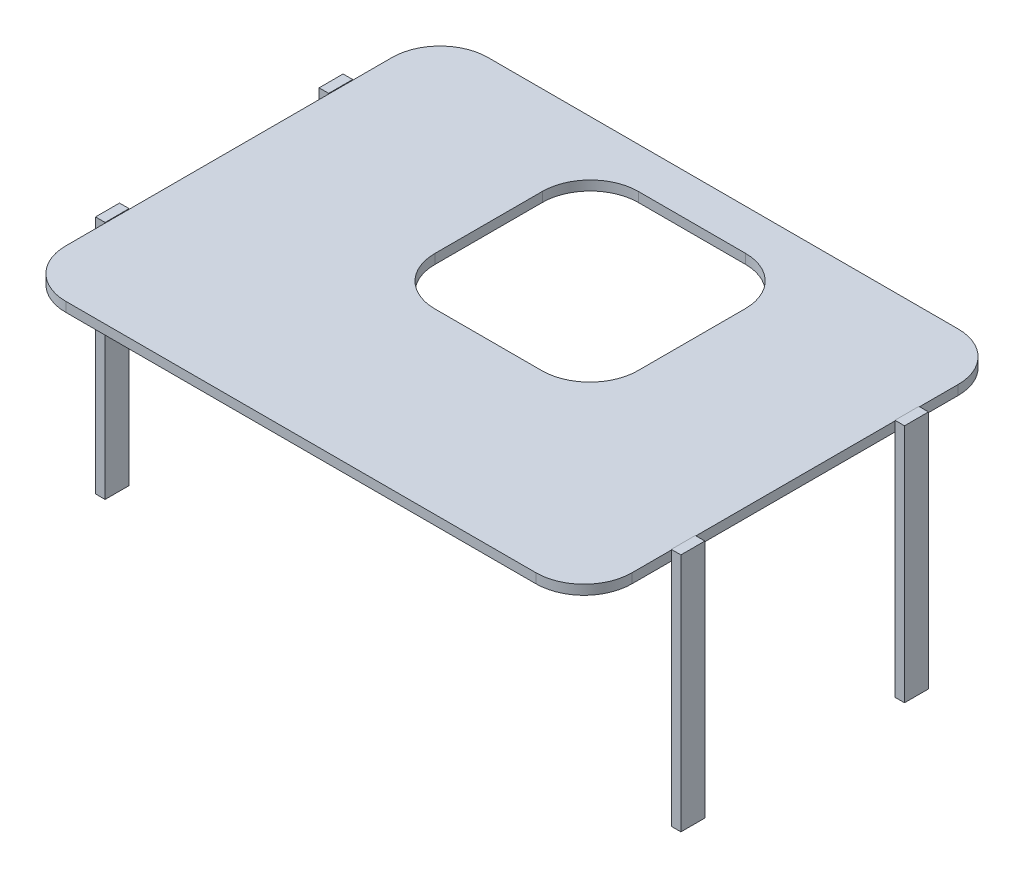
SolidWorks part; units mm, degrees
ref_plane "Plano frontal" through (0, 0, 0) normal (0, 0, 1) x (1, 0, 0)
ref_plane "Plano superior" through (0, 0, 0) normal (0, 1, 0) x (1, 0, 0)
ref_plane "Plano direito" through (0, 0, 0) normal (1, 0, 0) x (0, 0, -1)
sketch "Esboço1" plane through (0, 0, 0) normal (0, 1, 0) x (1, 0, 0)
  line L1 (-59, 44) -> (59, 44)
  line L2 (-59, 44) -> (-59, -44)
  line L3 (-59, -44) -> (59, -44)
  line L4 (59, 44) -> (59, -44)
  line L5 (-59, 44) -> (59, -44) construction
  line L6 (-59, -44) -> (59, 44) construction
  point P0 (0, 0)
  dimension "D1" = 88
  dimension "D2" = 118
extrude "Ressalto-extrusão1" add sketch "Esboço1" along normal blind 2
fillet "Filete1" radius 10 1 edges at (59, 1, -44)
fillet "Filete2" radius 10 3 edges at (-59, 1, 44) (-59, 1, -44) (59, 1, 44)
sketch "Esboço2" plane through (0, 0, 0) normal (0, 1, 0) x (1, 0, 0)
  line L0 (49, 44) -> (-49, 44) construction
  line L1 (-19.17, 35.49) -> (23.14, 35.49)
  line L2 (-19.17, 35.49) -> (-19.17, -6.91)
  line L3 (-19.17, -6.91) -> (23.14, -6.91)
  line L4 (23.14, 35.49) -> (23.14, -6.91)
  line L5 (-59, 34) -> (-59, -34) construction
  dimension "D1" = 42.4
  dimension "D2" = 42.31
  dimension "D3" = 8.51
  dimension "D4" = 39.83
extrude "Corte-extrusão2" cut sketch "Esboço2" along normal blind 2
fillet "Filete3" radius 10 4 edges at (-19.17, 1, 6.91) (23.14, 1, 6.91) (23.14, 1, -35.49) (-19.17, 1, -35.49)
ref_plane "Plano1" through (69, 0, 0) normal (1, 0, 0) x (0, 0, -1)
sketch "Esboço5" plane through (59, 0, 0) normal (1, 0, 0) x (0, 0, -1)
  line L0 (-44, 2) -> (-44, 0) construction
  line L1 (-25.8, 2.1292) -> (-20.8, 2.1292)
  line L2 (-25.8, 2.1292) -> (-25.8, -47.8708)
  line L3 (-25.8, -47.8708) -> (-20.8, -47.8708)
  line L4 (-20.8, 2.1292) -> (-20.8, -47.8708)
  line L5 (20.8, 2.1292) -> (25.8, 2.1292)
  line L6 (20.8, 2.1292) -> (20.8, -47.8708)
  line L7 (20.8, -47.8708) -> (25.8, -47.8708)
  line L8 (25.8, 2.1292) -> (25.8, -47.8708)
  line L9 (44, 2) -> (44, 0) construction
  dimension "D1" = 18.2
  dimension "D2" = 5
  dimension "D3" = 5
  dimension "D4" = 50
  dimension "D5" = 50
  dimension "D6" = 18.2
extrude "Ressalto-extrusão3" add sketch "Esboço5" along normal blind 2 from surface at 0 starting at face at (59, 1, 0)
ref_plane "Plano2" through (-69, 0, 0) normal (-1, 0, 0) x (0, 0, 1)
sketch "Esboço6" plane through (-69, 0, 0) normal (-1, 0, 0) x (0, 0, 1)
  line L1 (-25.8, 2.1292) -> (-20.8, 2.1292)
  line L2 (-25.8, 2.1292) -> (-25.8, -47.8708)
  line L3 (-25.8, -47.8708) -> (-20.8, -47.8708)
  line L4 (-20.8, 2.1292) -> (-20.8, -47.8708)
  line L5 (20.8, -47.8708) -> (25.8, -47.8708)
  line L6 (20.8, -47.8708) -> (20.8, 2.1292)
  line L7 (20.8, 2.1292) -> (25.8, 2.1292)
  line L8 (25.8, -47.8708) -> (25.8, 2.1292)
  dimension "D1" = 5
  dimension "D2" = 5
  dimension "D3" = 50
  dimension "D4" = 50
extrude "Ressalto-extrusão4" add sketch "Esboço6" along normal blind 2 from surface at -10 starting at face at (-59, 1, 0)
